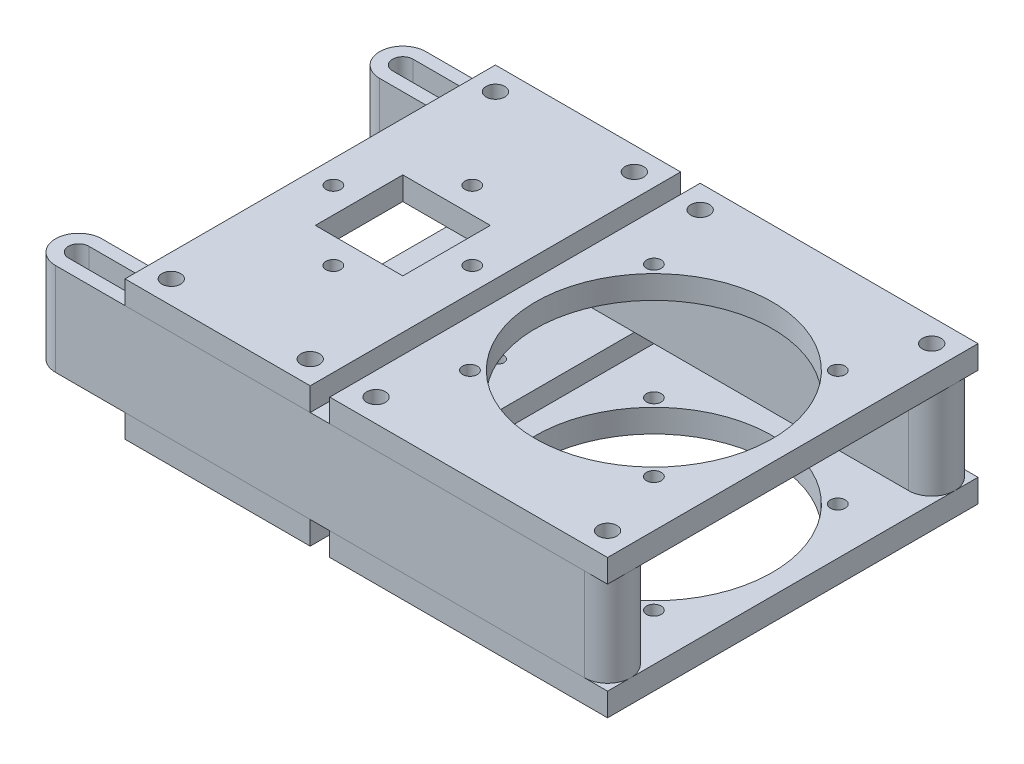
SolidWorks part; units mm, degrees
other "Modual Holding Plate 2"
other "Modual Holding Plate"
other "Encoder Mount Plate"
other "Gearbox Mount Plate"
other "Tension Slider"
other "Tension Slider 2"
material "Alum Plate"
ref_plane "Front Plane" through (0, 0, 0) normal (0, 0, 1) x (1, 0, 0)
ref_plane "Top Plane" through (0, 0, 0) normal (0, 1, 0) x (1, 0, 0)
ref_plane "Right Plane" through (0, 0, 0) normal (1, 0, 0) x (0, 0, -1)
sketch "Sketch2" plane through (0, 0, 0) normal (0, 1, 0) x (1, 0, 0)
  line L0 (0, 0) -> (-68.8619, 0) construction
  line L1 (-38.1, -50.8) -> (-38.1, 50.8)
  line L2 (-38.1, 50.8) -> (38.1, 50.8)
  line L4 (-38.1, -50.8) -> (38.1, -50.8)
  line L5 (38.1, 50.8) -> (38.1, -50.8)
  line L7 (-94.2619, 50.8) -> (-43.4619, 50.8)
  line L8 (-80.8619, 12) -> (-56.8619, 12) construction
  line L9 (-80.8619, 12) -> (-80.8619, -12) construction
  line L10 (-80.8619, -12) -> (-56.8619, -12) construction
  line L11 (-56.8619, 12) -> (-56.8619, -12) construction
  line L12 (-80.8619, 12) -> (-56.8619, -12) construction
  line L13 (-80.8619, -12) -> (-56.8619, 12) construction
  line L14 (-38.1, -50.8) -> (38.1, 50.8) construction
  line L15 (-94.2619, 50.8) -> (-94.2619, -50.8)
  line L16 (-94.2619, -50.8) -> (-43.4619, -50.8)
  line L17 (-43.4619, 50.8) -> (-43.4619, -50.8)
  line L18 (-94.2619, 50.8) -> (-43.4619, -50.8) construction
  line L19 (-94.2619, -50.8) -> (-43.4619, 50.8) construction
  circle A0 centre (0, 0) radius 32.5
  circle A1 centre (-68.8619, 0) radius 18 construction
  point P5 (-34.431, 0)
  point P8 (-38.1, 0)
  dimension "D1" = 65
  dimension "D2" = 36
  dimension "D3" = 68.8619
  dimension "D4" = 38.1
  dimension "D5" = 50.8
  dimension "D6" = 24
  dimension "D8" = 50.8
extrude "Boss-Extrude1" add sketch "Sketch2" against normal blind 6.35 from offset 19.05
mirror "Mirror1" about plane through (0, 0, 0) normal (0, 1, 0) of bodies 101 109
sketch "Sketch3" plane through (0, 19.05, 0) normal (0, 1, 0) x (1, 0, 0)
  line L1 (-80.8619, -12) -> (-56.8619, -12)
  line L2 (-80.8619, -12) -> (-80.8619, 12)
  line L3 (-80.8619, 12) -> (-56.8619, 12)
  line L4 (-56.8619, -12) -> (-56.8619, 12)
  line L5 (-80.8619, -12) -> (-56.8619, 12) construction
  line L6 (-80.8619, 12) -> (-56.8619, -12) construction
  point P4 (-68.8619, 0)
extrude "Cut-Extrude1" cut sketch "Sketch3" against normal up to next (6.35 mm away)
sketch "Sketch4" plane through (0, -19.05, 0) normal (0, -1, 0) x (1, 0, 0)
  circle A1 centre (-68.8619, 0) radius 11.176
  dimension "D1" = 22.352
extrude "Cut-Extrude2" cut sketch "Sketch4" against normal up to next (6.35 mm away)
sketch "Sketch5" plane through (0, -19.05, 0) normal (0, -1, 0) x (1, 0, 0)
  line L1 (-81.8667, 13.0048) -> (-55.8571, 13.0048) construction
  line L2 (-81.8667, 13.0048) -> (-81.8667, -13.0048) construction
  line L3 (-81.8667, -13.0048) -> (-55.8571, -13.0048) construction
  line L4 (-55.8571, 13.0048) -> (-55.8571, -13.0048) construction
  line L5 (-81.8667, 13.0048) -> (-55.8571, -13.0048) construction
  line L6 (-81.8667, -13.0048) -> (-55.8571, 13.0048) construction
  circle A0 centre (-81.8667, 13.0048) radius 1.7272
  circle A1 centre (-55.8571, 13.0048) radius 1.7272
  circle A2 centre (-55.8571, -13.0048) radius 1.7272
  circle A3 centre (-81.8667, -13.0048) radius 1.7272
  point P0 (-68.8619, 0)
  dimension "D2" = 3.4544
  dimension "D1" = 26.0096
extrude "Cut-Extrude3" cut sketch "Sketch5" against normal up to next (6.35 mm away)
sketch "Sketch6" plane through (0, 19.05, 0) normal (0, 1, 0) x (1, 0, 0)
  line L0 (-38.1, -44.45) -> (-31.75, -44.45) construction
  line L2 (-31.75, -44.45) -> (-31.75, -50.8) construction
  line L3 (-38.1, -50.8) -> (38.1, -50.8) construction
  line L4 (-38.1, 44.45) -> (-31.75, 44.45) construction
  line L5 (-31.75, 44.45) -> (-31.75, 50.8) construction
  line L6 (38.1, 50.8) -> (-38.1, 50.8) construction
  line L7 (38.1, 44.45) -> (31.75, 44.45) construction
  line L8 (38.1, -50.8) -> (38.1, 50.8) construction
  line L9 (31.75, 44.45) -> (31.75, 50.8) construction
  line L10 (31.75, -50.8) -> (31.75, -44.45) construction
  line L11 (31.75, -44.45) -> (38.1, -44.45) construction
  line L12 (-38.1, 50.8) -> (-38.1, -50.8) construction
  line L13 (25.226, 25.226) -> (-25.226, 25.226) construction
  line L14 (25.226, 25.226) -> (25.226, -25.226) construction
  line L15 (25.226, -25.226) -> (-25.226, -25.226) construction
  line L16 (-25.226, 25.226) -> (-25.226, -25.226) construction
  line L17 (25.226, 25.226) -> (-25.226, -25.226) construction
  line L18 (25.226, -25.226) -> (-25.226, 25.226) construction
  line L19 (-49.8119, -50.8) -> (-49.8119, -44.45) construction
  line L20 (-94.2619, -50.8) -> (-43.4619, -50.8) construction
  line L21 (-49.8119, -44.45) -> (-43.4619, -44.45) construction
  line L22 (-43.4619, -50.8) -> (-43.4619, 50.8) construction
  line L23 (-68.8619, -50.8) -> (-68.8619, 50.8) construction
  line L24 (-43.4619, 50.8) -> (-94.2619, 50.8) construction
  line L25 (-94.2619, 0) -> (-43.4619, 0) construction
  line L26 (-94.2619, 50.8) -> (-94.2619, -50.8) construction
  circle A0 centre (-31.75, 44.45) radius 2.5527
  circle A1 centre (31.75, 44.45) radius 2.5527
  circle A2 centre (31.75, -44.45) radius 2.5527
  circle A3 centre (-31.75, -44.45) radius 2.5527
  circle A4 centre (-25.226, 25.226) radius 2.0193
  circle A5 centre (25.226, 25.226) radius 2.0193
  circle A6 centre (25.226, -25.226) radius 2.0193
  circle A7 centre (-25.226, -25.226) radius 2.0193
  circle A8 centre (0, 0) radius 32.5 construction
  circle A9 centre (-49.8119, -44.45) radius 2.5527
  circle A10 centre (-49.8119, 44.45) radius 2.5527
  circle A11 centre (-87.9119, -44.45) radius 2.5527
  circle A12 centre (-87.9119, 44.45) radius 2.5527
  point P24 (0, 0)
  point P34 (-22.981, 22.981)
  dimension "D2" = 5.1054
  dimension "D3" = 4.0386
  dimension "D1" = 6.35
  dimension "D4" = 3.175
extrude "Cut-Extrude4" cut sketch "Sketch6" against normal through all
sketch "Sketch7" plane through (0, 19.05, 0) normal (0, 1, 0) x (1, 0, 0)
  line L0 (-68.8619, -19.05) -> (-68.8619, 0) construction
  line L1 (-68.8619, 0) -> (-68.8619, 19.05) construction
  line L2 (-49.8119, 0) -> (-68.8619, 0) construction
  line L3 (-68.8619, 0) -> (-87.9119, 0) construction
  circle A0 centre (-68.8619, 19.05) radius 2.0193
  circle A1 centre (-68.8619, -19.05) radius 2.0193
  circle A2 centre (-87.9119, 0) radius 2.0193
  circle A3 centre (-49.8119, 0) radius 2.0193
  dimension "D1" = 4.0386
  dimension "D2" = 19.05
extrude "Cut-Extrude5" cut sketch "Sketch7" against normal up to next (6.35 mm away)
sketch "Sketch8" plane through (0, -12.7, 0) normal (0, 1, 0) x (1, 0, 0)
  line L0 (31.75, -44.45) -> (-113.3119, -44.45) construction
  line L1 (31.75, -50.8) -> (-113.3119, -50.8)
  line L2 (31.75, -38.1) -> (-113.3119, -38.1)
  line L3 (-94.2619, -50.8) -> (-43.4619, -50.8) construction
  line L4 (31.75, 44.45) -> (-113.3119, 44.45) construction
  line L5 (31.75, 38.1) -> (-113.3119, 38.1)
  line L6 (31.75, 50.8) -> (-113.3119, 50.8)
  line L7 (-43.4619, 50.8) -> (-94.2619, 50.8) construction
  line L8 (-113.3119, -44.45) -> (-113.3119, 44.45) construction
  line L9 (-49.8119, 44.45) -> (-113.3119, 44.45) construction
  line L10 (-49.8119, 41.656) -> (-113.3119, 41.656)
  line L11 (-49.8119, 47.244) -> (-113.3119, 47.244)
  line L12 (-49.8119, -44.45) -> (-113.3119, -44.45) construction
  line L13 (-49.8119, -47.244) -> (-113.3119, -47.244)
  line L14 (-49.8119, -41.656) -> (-113.3119, -41.656)
  arc A0 (31.75, -50.8) -> (31.75, -38.1) centre (31.75, -44.45) ccw
  arc A1 (-113.3119, -38.1) -> (-113.3119, -50.8) centre (-113.3119, -44.45) ccw
  arc A2 (31.75, 38.1) -> (31.75, 50.8) centre (31.75, 44.45) ccw
  arc A3 (-113.3119, 50.8) -> (-113.3119, 38.1) centre (-113.3119, 44.45) ccw
  arc A6 (-49.8119, 41.656) -> (-49.8119, 47.244) centre (-49.8119, 44.45) ccw
  arc A7 (-113.3119, 47.244) -> (-113.3119, 41.656) centre (-113.3119, 44.45) ccw
  arc A8 (-49.8119, -47.244) -> (-49.8119, -41.656) centre (-49.8119, -44.45) ccw
  arc A9 (-113.3119, -41.656) -> (-113.3119, -47.244) centre (-113.3119, -44.45) ccw
  point P3 (-40.781, -44.45)
  point P13 (-40.781, 44.45)
  point P23 (-87.9119, 44.45)
  point P24 (-81.5619, 44.45)
  point P32 (-81.5619, -44.45)
  dimension "D1" = 25.4
  dimension "D2" = 5.588
extrude "Boss-Extrude2" add sketch "Sketch8" along normal up to surface (25.4 mm away) separate body up to face at (-87.9119, 12.7, 2.0193)
other "Save Bodies1"
